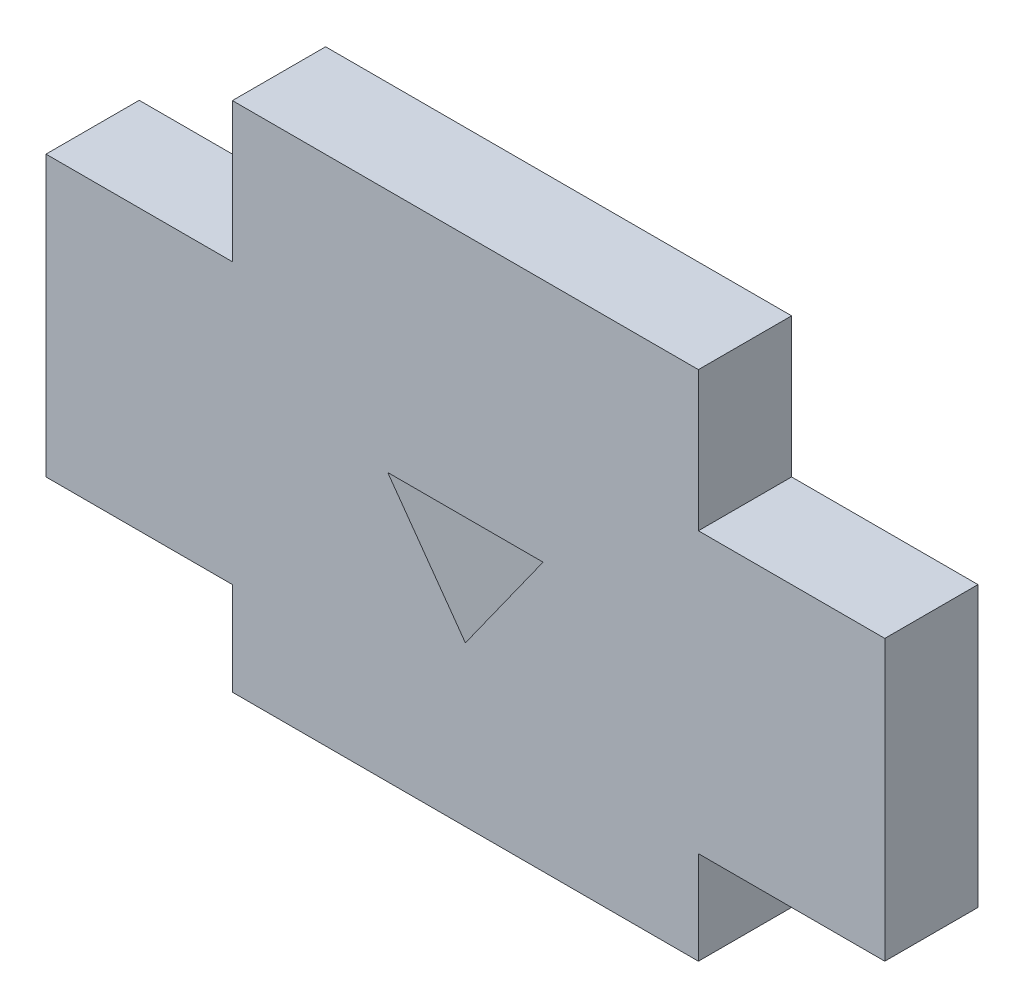
SolidWorks part; units mm, degrees
ref_plane "Front Plane" through (0, 0, 0) normal (0, 0, 1) x (1, 0, 0)
ref_plane "Top Plane" through (0, 0, 0) normal (0, 1, 0) x (1, 0, 0)
ref_plane "Right Plane" through (0, 0, 0) normal (1, 0, 0) x (0, 0, -1)
sketch "Sketch1" plane through (0, 0, 0) normal (0, 0, 1) x (1, 0, 0)
  line L0 (-2.1338, -20.1538) -> (-2.1338, -6.4257)
  line L1 (-29.1338, -35.3178) -> (-17.1338, -35.3178)
  line L2 (-29.1338, -35.3178) -> (-29.1338, -53.3178)
  line L3 (-29.1338, -53.3178) -> (-17.1338, -53.3178)
  line L5 (-17.1338, -59.3178) -> (12.8662, -59.3178)
  line L6 (-17.1338, -59.3178) -> (-17.1338, -53.3178)
  line L7 (-17.1338, -26.3328) -> (12.8662, -26.3328)
  line L8 (12.8662, -59.3178) -> (12.8662, -53.3178)
  line L10 (24.8662, -53.3178) -> (12.8662, -53.3178)
  line L11 (24.8662, -35.3178) -> (24.8662, -53.3178)
  line L12 (24.8662, -35.3178) -> (12.8662, -35.3178)
  line L13 (-17.1338, -35.3178) -> (-17.1338, -26.3328)
  line L14 (12.8662, -35.3178) -> (12.8662, -26.3328)
  line L21 (-2.1338, -49.0678) -> (2.8662, -42.0678)
  line L22 (2.8662, -42.0678) -> (-7.1338, -42.0678)
  line L23 (-7.1338, -42.0678) -> (-2.1338, -49.0678)
  dimension "D1" = 12
  dimension "D2" = 30
  dimension "D3" = 10
  dimension "D4" = 7
extrude "Boss-Extrude1" add sketch "Sketch1" along normal blind 6 contours L12 L14 L7 L13 L1 L2 L3 L6 L5 L8 L10 L11 L23 L22 L21
